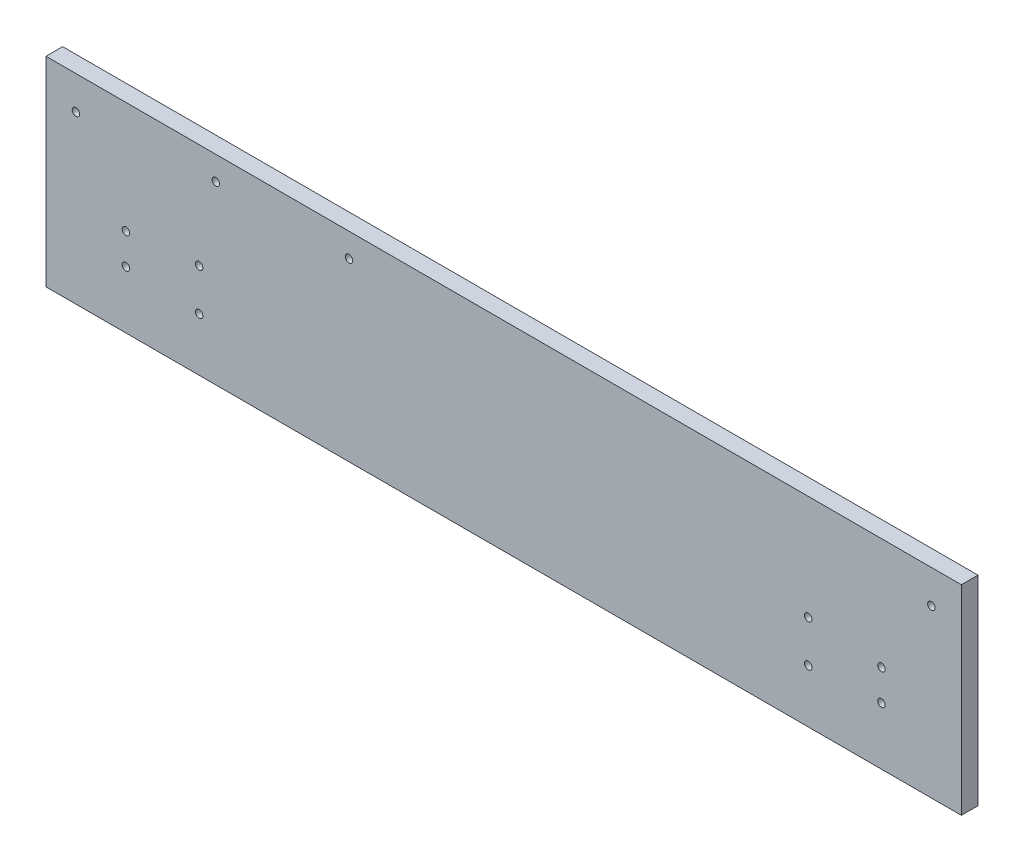
SolidWorks part; units mm, degrees
material "Multistrato di pioppo"
ref_plane "Piano frontale" through (0, 0, 0) normal (0, 0, 1) x (1, 0, 0)
ref_plane "Piano superiore" through (0, 0, 0) normal (0, 1, 0) x (1, 0, 0)
ref_plane "Piano destro" through (0, 0, 0) normal (1, 0, 0) x (0, 0, -1)
sketch "Schizzo1" plane through (0, 0, 0) normal (0, 0, 1) x (1, 0, 0)
  line L1 (-275, 60) -> (275, 60)
  line L2 (-275, 60) -> (-275, -60)
  line L3 (-275, -60) -> (275, -60)
  line L4 (275, 60) -> (275, -60)
  line L5 (-275, 60) -> (275, -60) construction
  line L6 (-275, -60) -> (275, 60) construction
  point P4 (0, 0)
  dimension "D1" = 550
  dimension "D2" = 120
extrude "Estrusione-Estrusione1" add sketch "Schizzo1" along normal blind 10
sketch "Schizzo2" plane through (0, 0, 0) normal (0, 0, -1) x (-1, 0, 0)
  line L0 (-183, -2) -> (-183, -25) construction
  line L1 (183, -2) -> (183, -25) construction
  line L2 (275, 60) -> (275, -60) construction
  line L4 (275, -60) -> (-275, -60) construction
  line L5 (-275, -60) -> (-275, 60) construction
  line L6 (172.9257, 45.7) -> (92.9257, 45.7) construction
  line L7 (-275, 60) -> (275, 60) construction
  line L8 (275, 60) -> (275, -60) construction
  circle A0 centre (-227, -7) radius 2.25
  circle A1 centre (-227, -25.5) radius 2.25
  circle A2 centre (227, -7) radius 2.25
  circle A3 centre (227, -25.5) radius 2.25
  circle A5 centre (-257, 40) radius 2.25
  circle A7 centre (257, 40) radius 2.25
  circle A8 centre (-183, -25) radius 2.25 construction
  circle A9 centre (-183, -2) radius 2.25 construction
  circle A10 centre (183, -25) radius 2.25 construction
  circle A11 centre (183, -2) radius 2.25 construction
  circle A12 centre (172.9257, 45.7) radius 2.25
  circle A13 centre (92.9257, 45.7) radius 2.25
  point P36 (183, -13.5)
  dimension "D1" = 4.5
  dimension "D7" = 14.3
  dimension "D2" = 92
  dimension "D3" = 58
  dimension "D4" = 23
  dimension "D5" = 92
  dimension "D6" = 58
  dimension "D8" = 102.0743
  dimension "D9" = 80
extrude "Taglio-Estrusione1" cut sketch "Schizzo2" against normal blind 10
sketch "Schizzo3" plane through (0, 0, 10) normal (0, 0, 1) x (1, 0, 0)
  line L0 (-183, -28) -> (-183, -3) construction
  line L1 (183, -28) -> (183, -3) construction
  line L2 (-275, -60) -> (275, -60) construction
  line L3 (-275, 60) -> (-275, -60) construction
  line L4 (275, -60) -> (275, 60) construction
  circle A0 centre (-183, -3) radius 2.25
  circle A1 centre (-183, -28) radius 2.25
  circle A2 centre (183, -28) radius 2.25
  circle A3 centre (183, -3) radius 2.25
  dimension "D1" = 4.5
  dimension "D2" = 25
  dimension "D3" = 32
  dimension "D4" = 92
  dimension "D5" = 92
  dimension "D6" = 32
  dimension "D7" = 25
extrude "Taglio-Estrusione2" cut sketch "Schizzo3" against normal blind 10
